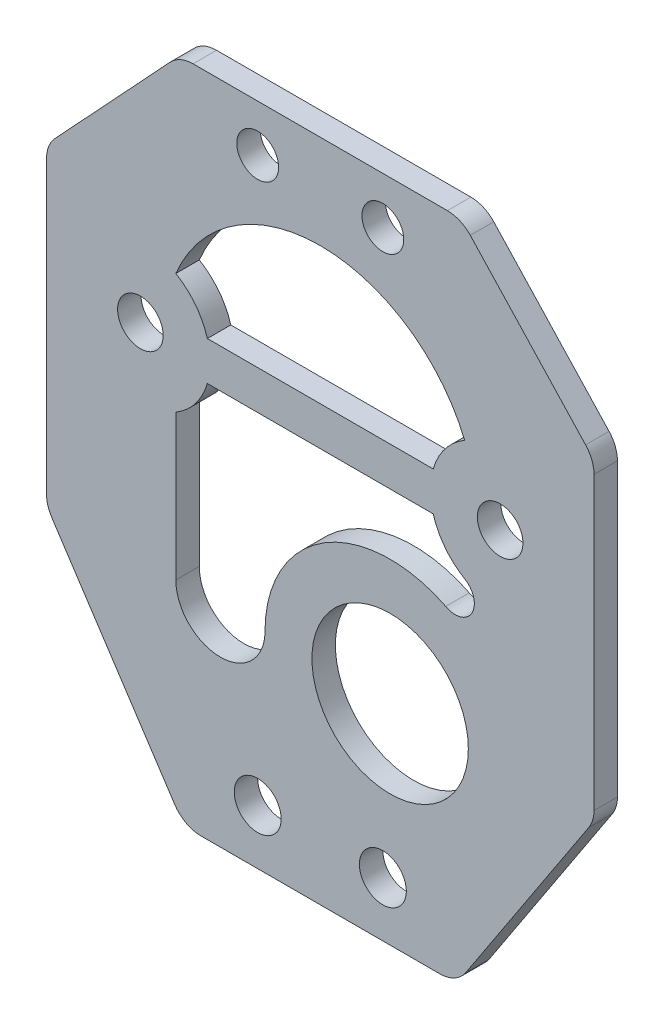
SolidWorks part; units mm, degrees
ref_plane "Front Plane" through (0, 0, 0) normal (0, 0, 1) x (1, 0, 0)
ref_plane "Top Plane" through (0, 0, 0) normal (0, 1, 0) x (1, 0, 0)
ref_plane "Right Plane" through (0, 0, 0) normal (1, 0, 0) x (0, 0, -1)
sketch "Sketch1" plane through (0, 0, 0) normal (0, 0, 1) x (1, 0, 0)
  line L0 (0, 0) -> (0, 85) construction
  line L1 (17.4253, 0) -> (-17.4253, 0)
  line L2 (-17.4253, 0) -> (-35, 26.7419)
  line L3 (-35, 26.7419) -> (-35, 66.7419)
  line L4 (-35, 66.7419) -> (-18, 85)
  line L5 (-18, 85) -> (18, 85)
  line L6 (17.4253, 0) -> (35, 26.7419)
  line L7 (35, 26.7419) -> (35, 66.7419)
  line L8 (35, 66.7419) -> (18, 85)
  line L9 (-23, 53) -> (23, 53) construction
  line L10 (-14.4388, 55.4892) -> (14.4388, 55.4892)
  line L11 (14.4388, 55.4892) -> (-14.4388, 55.4892) construction
  line L12 (14.4388, 55.4892) -> (14.4388, 50.5108) construction
  line L13 (14.4388, 50.5108) -> (-14.4388, 50.5108) construction
  line L14 (-14.4388, 55.4892) -> (-14.4388, 50.5108) construction
  line L15 (14.4388, 55.4892) -> (-14.4388, 50.5108) construction
  line L16 (14.4388, 50.5108) -> (-14.4388, 55.4892) construction
  line L17 (-14.4388, 50.5108) -> (14.4388, 50.5108)
  line L18 (23, 53) -> (16.0474, 41.0725) construction
  line L19 (-18.4676, 45.3223) -> (-18.4676, 26.7419)
  circle A0 centre (-23, 53) radius 2.9157
  circle A1 centre (-8, 79) radius 2.6731
  circle A2 centre (-8, 7) radius 3
  circle A3 centre (8, 7) radius 3
  circle A4 centre (23, 53) radius 2.9157
  circle A5 centre (8, 79) radius 2.6731
  circle A6 centre (8.9315, 26.7419) radius 10
  circle A7 centre (23, 53) radius 8.9157 construction
  circle A8 centre (8.9315, 26.7419) radius 16 construction
  circle A9 centre (-23, 53) radius 8.9157 construction
  arc A10 (-18.4676, 60.6777) -> (18.4676, 60.6777) centre (0, 53) cw
  arc A11 (-18.4676, 60.6777) -> (-14.4388, 55.4892) centre (-23, 53) cw
  arc A12 (18.4676, 60.6777) -> (14.4388, 55.4892) centre (23, 53) ccw
  arc A13 (-14.4388, 50.5108) -> (-18.4676, 45.3223) centre (-23, 53) cw
  arc A14 (14.4388, 50.5108) -> (18.4676, 45.3223) centre (23, 53) ccw
  arc A15 (18.4676, 45.3223) -> (16.0474, 41.0725) centre (17.2575, 43.1974) cw
  arc A16 (16.0474, 41.0725) -> (-7.0685, 26.7419) centre (8.9315, 26.7419) ccw
  arc A17 (-18.4676, 26.7419) -> (-7.0685, 26.7419) centre (-12.768, 26.7419) ccw
  dimension "D7" = 12
  dimension "D8" = 8
  dimension "D9" = 8
  dimension "D12" = 6
  dimension "D17" = 4.9785
  dimension "D18" = 29.7894
  dimension "D19" = 20
  dimension "D1" = 35
  dimension "D2" = 40
  dimension "D3" = 24.9471
  dimension "D4" = 32
  dimension "D5" = 85
  dimension "D6" = 18
  dimension "D10" = 17.4253
  dimension "D11" = 7
  dimension "D13" = 6
  dimension "D14" = 32
  dimension "D15" = 6
  dimension "D16" = 6
extrude "Boss-Extrude2" add sketch "Sketch1" along normal blind 3
fillet "Fillet1" radius 4 8 edges at (18, 85, 1.5) (-18, 85, 1.5) (35, 66.7419, 1.5) (35, 26.7419, 1.5) (-35, 26.7419, 1.5) (-17.4253, 0, 1.5) (17.4253, 0, 1.5) (-35, 66.7419, 1.5)
